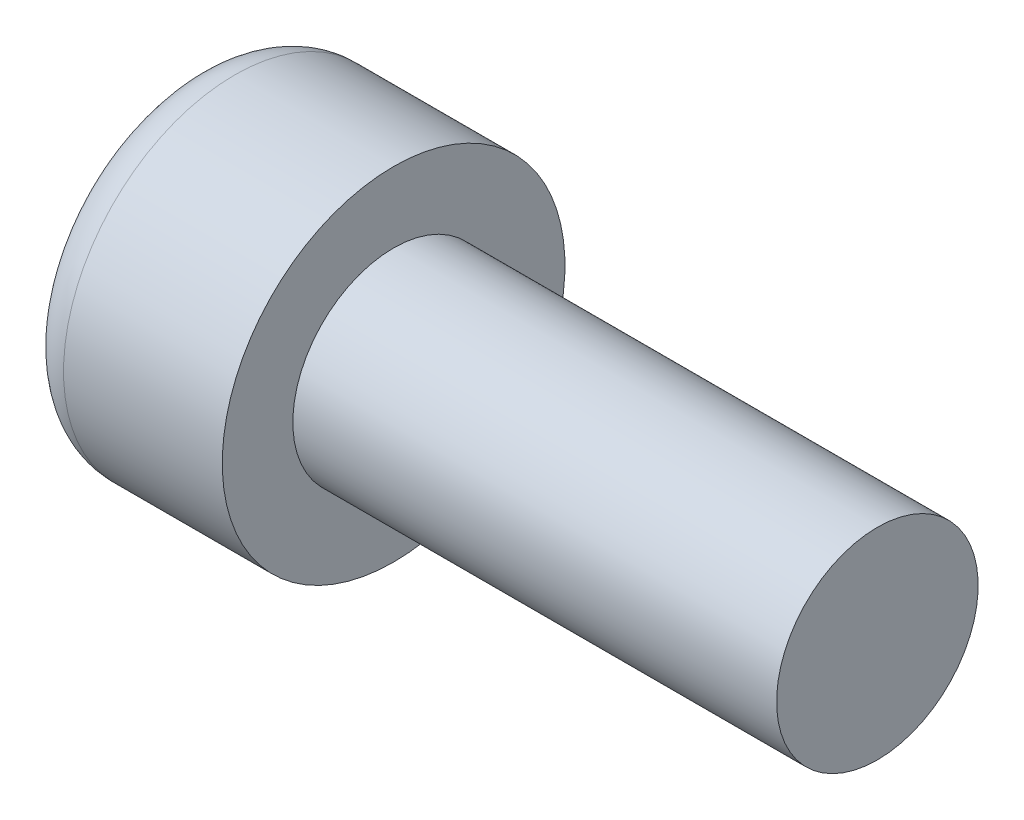
SolidWorks part; units mm, degrees
material "Plain Carbon Steel"
ref_plane "Front Plane" through (0, 0, 0) normal (0, 0, 1) x (1, 0, 0)
ref_plane "Top Plane" through (0, 0, 0) normal (0, 1, 0) x (1, 0, 0)
ref_plane "Right Plane" through (0, 0, 0) normal (1, 0, 0) x (0, 0, -1)
sketch "Sketch1" plane through (0, 0, 0) normal (0, 0, 1) x (1, 0, 0)
  line L0 (0, 0) -> (0, 3.1875)
  line L1 (1.0625, 4.25) -> (5, 4.25)
  line L2 (5, 4.25) -> (5, 2.5)
  line L3 (5, 2.5) -> (17, 2.5)
  line L4 (17, 2.5) -> (17, 0)
  line L5 (17, 0) -> (0, 0) construction
  line L6 (1.0625, 3.1875) -> (1.0625, 2.125) construction
  line L7 (1.0625, 2.125) -> (1.0625, 1.0625) construction
  line L8 (1.0625, 1.0625) -> (1.0625, 0) construction
  line L9 (1.0625, 4.25) -> (1.0625, 3.1875) construction
  line L10 (0, 0) -> (17, 0)
  arc A0 (0, 3.1875) -> (1.0625, 4.25) centre (1.0625, 3.1875) cw
  dimension "D1" = 5
  dimension "D2" = 8.5
  dimension "D3" = 5
  dimension "D4" = 12
revolve "Revolve1" add sketch "Sketch1" angle 360 about L10
sketch "Sketch2" plane through (0, 0, 0) normal (-1, 0, 0) x (0, 0, 1)
  line L1 (0, 2.3094) -> (-2, 1.1547)
  line L2 (-2, 1.1547) -> (-2, -1.1547)
  line L3 (-2, -1.1547) -> (0, -2.3094)
  line L4 (0, -2.3094) -> (2, -1.1547)
  line L5 (2, -1.1547) -> (2, 1.1547)
  line L6 (2, 1.1547) -> (0, 2.3094)
  circle A0 centre (0, 0) radius 2 construction
  dimension "D1" = 4
extrude "Cut-Extrude1" cut sketch "Sketch2" against normal blind 2.5
